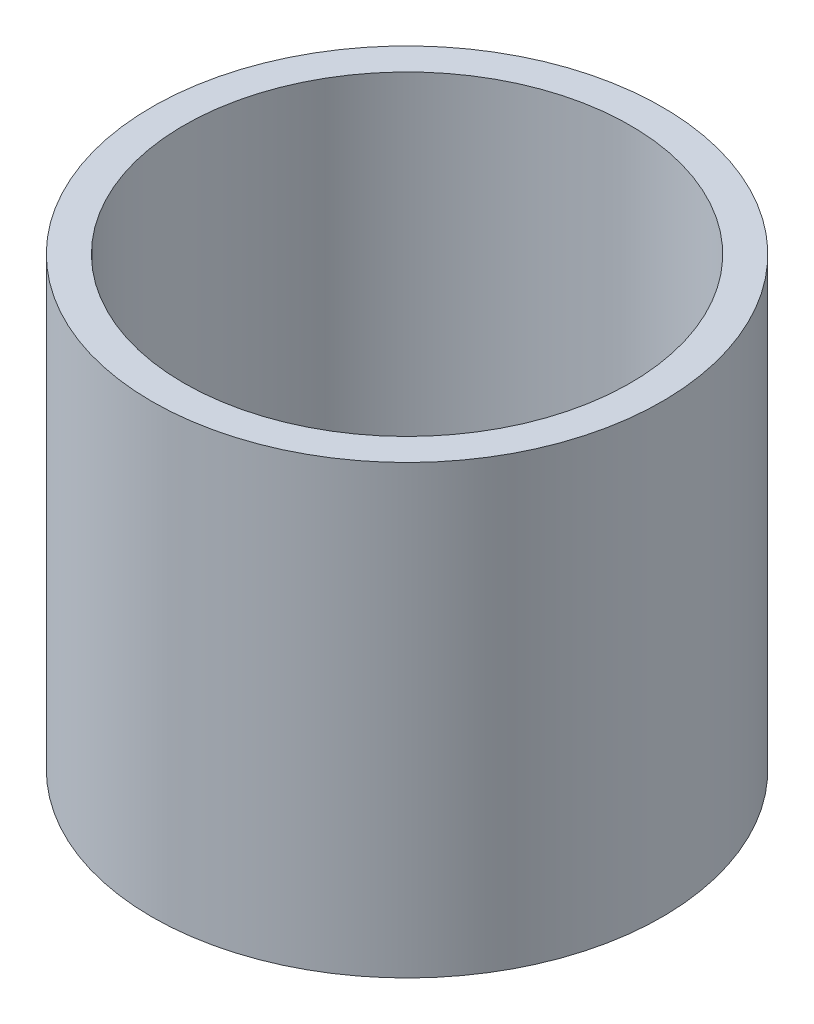
SolidWorks part; units mm, degrees
ref_plane "Front Plane" through (0, 0, 0) normal (0, 0, 1) x (1, 0, 0)
ref_plane "Top Plane" through (0, 0, 0) normal (0, 1, 0) x (1, 0, 0)
ref_plane "Right Plane" through (0, 0, 0) normal (1, 0, 0) x (0, 0, -1)
sketch "Sketch1" plane through (0, 0, 0) normal (0, 1, 0) x (1, 0, 0)
  circle A0 centre (0, 0) radius 11.1125
  circle A1 centre (0, 0) radius 12.7
  dimension "D1" = 22.225
  dimension "D2" = 25.4
extrude "Boss-Extrude1" add sketch "Sketch1" along normal blind 22.225
